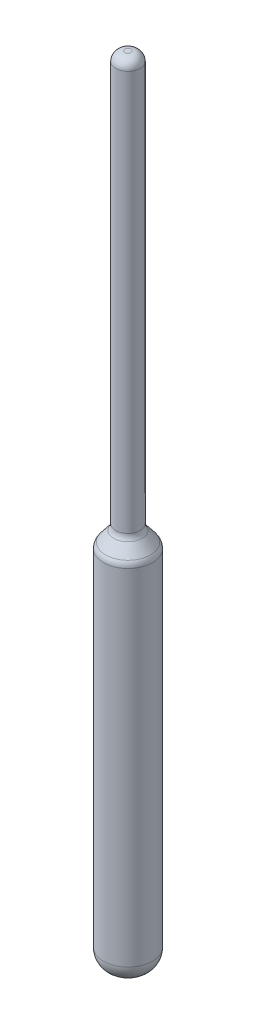
SolidWorks part; units mm, degrees
ref_plane "Front Plane" through (0, 0, 0) normal (0, 0, 1) x (1, 0, 0)
ref_plane "Top Plane" through (0, 0, 0) normal (0, 1, 0) x (1, 0, 0)
ref_plane "Right Plane" through (0, 0, 0) normal (1, 0, 0) x (0, 0, -1)
sketch "Sketch1" plane through (0, 0, 0) normal (0, 0, 1) x (1, 0, 0)
  line L0 (0, 0) -> (0, 260)
  line L1 (0, 260) -> (-4, 260)
  line L2 (-4, 260) -> (-4, 125)
  line L3 (-4, 125) -> (-8, 120)
  line L4 (-8, 120) -> (-8, 0)
  line L5 (-8, 0) -> (0, 0)
  dimension "D1" = 260
  dimension "D2" = 135
  dimension "D3" = 120
  dimension "D4" = 4
  dimension "D5" = 8
revolve "Revolve1" add sketch "Sketch1" angle 360 about L0
fillet "Fillet1" radius 3 1 edges at (0, 260, -4)
fillet "Fillet2" radius 3 1 edges at (0, 120, -8)
fillet "Fillet3" radius 3 1 edges at (0, 125, -4)
fillet "Fillet4" radius 6 1 edges at (0, 0, -8)
